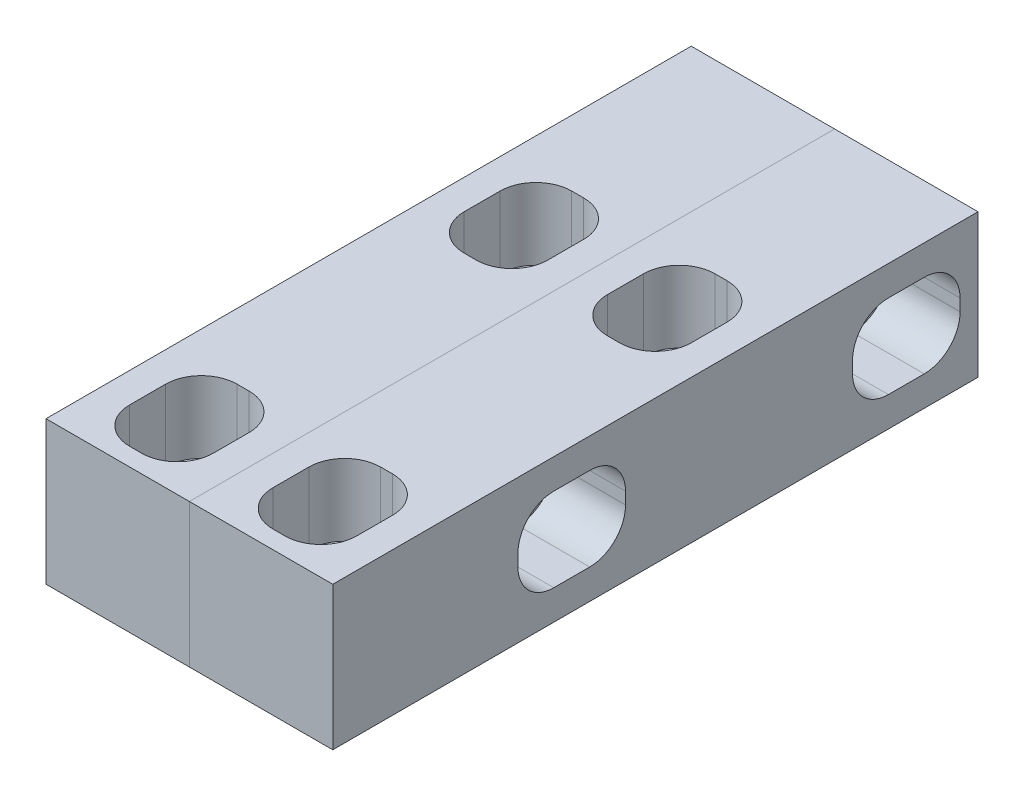
SolidWorks part; units mm, degrees
ref_plane "Front Plane" through (0, 0, 0) normal (0, 0, 1) x (1, 0, 0)
ref_plane "Top Plane" through (0, 0, 0) normal (0, 1, 0) x (1, 0, 0)
ref_plane "Right Plane" through (0, 0, 0) normal (1, 0, 0) x (0, 0, -1)
sketch "Sketch1" plane through (0, 0, 0) normal (0, 0, 1) x (1, 0, 0)
  line L1 (6, 6) -> (-6, 6)
  line L2 (6, 6) -> (6, -6)
  line L3 (6, -6) -> (-6, -6)
  line L4 (-6, 6) -> (-6, -6)
  line L5 (6, 6) -> (-6, -6) construction
  line L6 (6, -6) -> (-6, 6) construction
  point P0 (0, 0)
  dimension "D1" = 12
  dimension "D2" = 12
extrude "Boss-Extrude1" add sketch "Sketch1" along normal blind 54
sketch "Sketch2" plane through (0, 6, 0) normal (0, 1, 0) x (1, 0, 0)
  line L0 (0, 0) -> (0, -20) construction
  line L1 (6, 0) -> (-6, 0) construction
  line L2 (0, -54) -> (0, -48) construction
  line L3 (6, -54) -> (-6, -54) construction
  circle A1 centre (0, -20) radius 2
  circle A2 centre (0, -48) radius 2
  dimension "D1" = 4
  dimension "D4" = 4
  dimension "D2" = 20
  dimension "D3" = 6
extrude "Cut-Extrude1" cut sketch "Sketch2" against normal blind 14
sketch "Sketch3" plane through (-6, 0, 0) normal (-1, 0, 0) x (0, 0, 1)
  line L0 (54, 0) -> (34, 0) construction
  line L1 (54, 6) -> (54, -6) construction
  line L2 (0, 0) -> (6, 0) construction
  line L3 (0, 6) -> (0, -6) construction
  circle A0 centre (34, 0) radius 2
  circle A1 centre (6, 0) radius 2
  dimension "D2" = 4
  dimension "D4" = 4
  dimension "D1" = 20
  dimension "D3" = 6
extrude "Cut-Extrude2" cut sketch "Sketch3" against normal blind 14
sketch "Sketch4" plane through (6, 0, 0) normal (1, 0, 0) x (0, 0, -1)
  line L0 (-6, 0) -> (-34, 0) construction
  line L1 (-4.5, -3.5) -> (-7.5, -3.5)
  line L2 (-1.5, -0.5) -> (-1.5, 0.5)
  line L3 (-4.5, 3.5) -> (-7.5, 3.5)
  line L4 (-10.5, -0.5) -> (-10.5, 0.5)
  line L5 (-1.5, -3.5) -> (-10.5, 3.5) construction
  line L6 (-1.5, 3.5) -> (-10.5, -3.5) construction
  line L7 (-20, 0) -> (-20, -6) construction
  line L8 (-54, -6) -> (0, -6) construction
  line L9 (-38.5, -0.5) -> (-38.5, 0.5)
  line L10 (-35.5, 3.5) -> (-32.5, 3.5)
  line L11 (-29.5, -0.5) -> (-29.5, 0.5)
  line L12 (-35.5, -3.5) -> (-32.5, -3.5)
  arc A0 (-1.5, 0.5) -> (-4.5, 3.5) centre (-4.5, 0.5) ccw
  arc A1 (-7.5, 3.5) -> (-10.5, 0.5) centre (-7.5, 0.5) ccw
  arc A2 (-7.5, -3.5) -> (-10.5, -0.5) centre (-7.5, -0.5) cw
  arc A3 (-4.5, -3.5) -> (-1.5, -0.5) centre (-4.5, -0.5) ccw
  arc A4 (-38.5, 0.5) -> (-35.5, 3.5) centre (-35.5, 0.5) cw
  arc A5 (-32.5, 3.5) -> (-29.5, 0.5) centre (-32.5, 0.5) cw
  arc A6 (-32.5, -3.5) -> (-29.5, -0.5) centre (-32.5, -0.5) ccw
  arc A7 (-35.5, -3.5) -> (-38.5, -0.5) centre (-35.5, -0.5) cw
  point P0 (-6, 0)
  dimension "D3" = 3
  dimension "D1" = 7
  dimension "D2" = 9
extrude "Cut-Extrude3" cut sketch "Sketch4" against normal blind 6
sketch "Sketch5" plane through (0, 6, 0) normal (0, 1, 0) x (1, 0, 0)
  line L0 (0, -48) -> (0, -20) construction
  line L1 (0, -34) -> (-6, -34) construction
  line L2 (-0.5, -52.5) -> (0.5, -52.5)
  line L3 (-3.5, -49.5) -> (-3.5, -46.5)
  line L4 (-0.5, -43.5) -> (0.5, -43.5)
  line L5 (3.5, -49.5) -> (3.5, -46.5)
  line L6 (-3.5, -52.5) -> (3.5, -43.5) construction
  line L7 (-3.5, -43.5) -> (3.5, -52.5) construction
  line L8 (-6, -54) -> (-6, 0) construction
  line L9 (-0.5, -24.5) -> (0.5, -24.5)
  line L10 (3.5, -18.5) -> (3.5, -21.5)
  line L11 (-0.5, -15.5) -> (0.5, -15.5)
  line L12 (-3.5, -18.5) -> (-3.5, -21.5)
  arc A0 (0.5, -52.5) -> (3.5, -49.5) centre (0.5, -49.5) ccw
  arc A1 (0.5, -43.5) -> (3.5, -46.5) centre (0.5, -46.5) cw
  arc A2 (-3.5, -46.5) -> (-0.5, -43.5) centre (-0.5, -46.5) cw
  arc A3 (-0.5, -52.5) -> (-3.5, -49.5) centre (-0.5, -49.5) cw
  arc A4 (0.5, -24.5) -> (3.5, -21.5) centre (0.5, -21.5) ccw
  arc A5 (0.5, -15.5) -> (3.5, -18.5) centre (0.5, -18.5) cw
  arc A6 (-3.5, -21.5) -> (-0.5, -24.5) centre (-0.5, -21.5) ccw
  arc A7 (-0.5, -15.5) -> (-3.5, -18.5) centre (-0.5, -18.5) ccw
  dimension "D3" = 3
  dimension "D1" = 7
  dimension "D2" = 9
extrude "Cut-Extrude4" cut sketch "Sketch5" against normal blind 6
mirror "Mirror3" about plane through (-6, 6, 54) normal (1, 0, 0) of bodies 105
